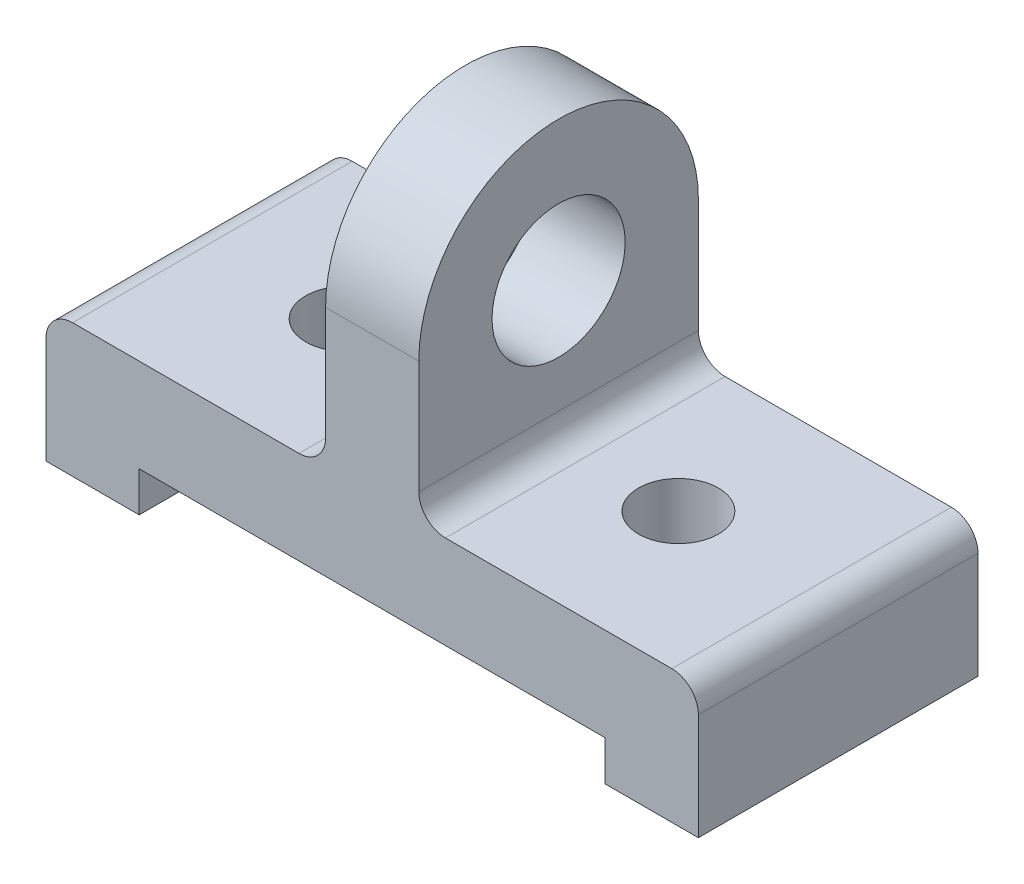
SolidWorks part; units mm, degrees
ref_plane "Front Plane" through (0, 0, 0) normal (0, 0, 1) x (1, 0, 0)
ref_plane "Top Plane" through (0, 0, 0) normal (0, 1, 0) x (1, 0, 0)
ref_plane "Right Plane" through (0, 0, 0) normal (1, 0, 0) x (0, 0, -1)
sketch "Sketch1" plane through (0, 0, 0) normal (0, 0, 1) x (1, 0, 0)
  line L0 (0, 0) -> (0, -6)
  line L1 (0, -6) -> (14, -6)
  line L2 (14, -6) -> (14, 14)
  line L3 (14, 14) -> (-35, 14)
  line L4 (-35, 14) -> (-35, 0)
  line L5 (0, 0) -> (-35, 0)
  dimension "D1" = 14
  dimension "D2" = 35
  dimension "D3" = 6
extrude "Boss-Extrude1" add sketch "Sketch1" along normal blind 42
ref_plane "Plane1" through (-28, 0, 0) normal (-1, 0, 0) x (0, 0, 1)
sketch "Sketch3" plane through (-28, 0, 0) normal (-1, 0, 0) x (0, 0, 1)
  line L0 (0, 14) -> (42, 14)
  line L1 (42, 14) -> (42, 35)
  line L3 (0, 35) -> (0, 14)
  circle A0 centre (21, 35) radius 10
  arc A1 (42, 35) -> (0, 35) centre (21, 35) ccw
  dimension "D1" = 20
extrude "Boss-Extrude2" add sketch "Sketch3" along normal blind 7
sketch "Sketch4" plane through (0, 14, 0) normal (0, 1, 0) x (1, 0, 0)
  line L0 (-28, 0) -> (-28, -42) construction
  line L1 (14, 0) -> (-28, 0) construction
  circle A0 centre (-10, -21) radius 6
  dimension "D1" = 12
  dimension "D2" = 18
  dimension "D3" = 21
extrude "Cut-Extrude1" cut sketch "Sketch4" against normal through all
fillet "Fillet1" radius 4 2 edges at (-28, 14, 21) (14, 14, 21)
mirror "Mirror2" about plane through (-35, 14, 42) normal (1, 0, 0) of bodies 103
